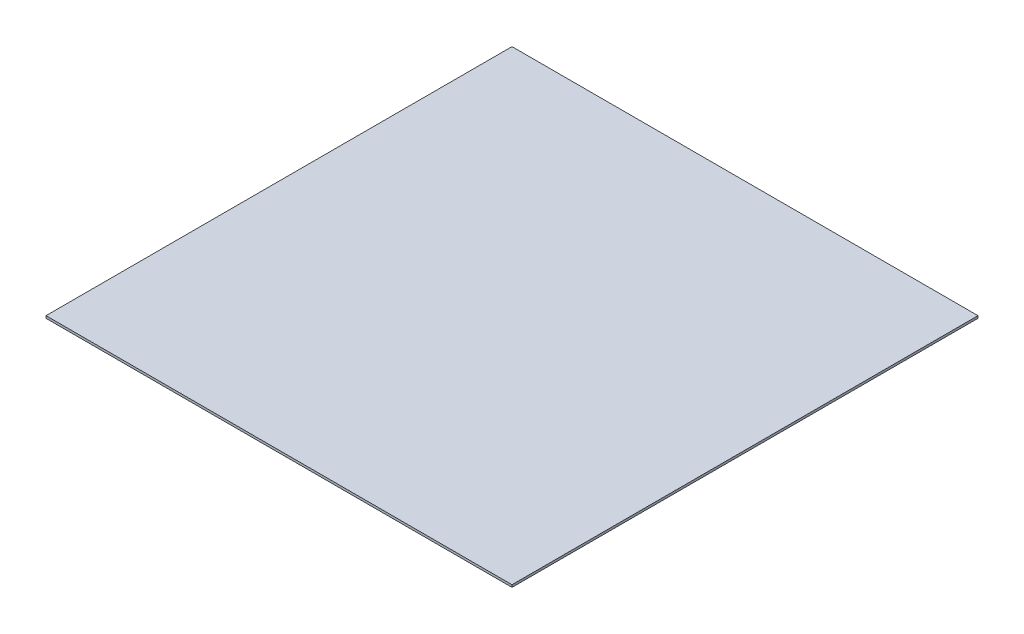
SolidWorks part; units mm, degrees
ref_plane "前视基准面" through (0, 0, 0) normal (0, 0, 1) x (1, 0, 0)
ref_plane "上视基准面" through (0, 0, 0) normal (0, 1, 0) x (1, 0, 0)
ref_plane "右视基准面" through (0, 0, 0) normal (1, 0, 0) x (0, 0, -1)
other "Configuration Table"
sketch "草图1" plane through (0, 0, 0) normal (0, 1, 0) x (1, 0, 0)
  line L1 (-1000, -1000) -> (1000, -1000)
  line L2 (-1000, -1000) -> (-1000, 1000)
  line L3 (-1000, 1000) -> (1000, 1000)
  line L4 (1000, -1000) -> (1000, 1000)
  dimension "D1" = 2000
  dimension "D2" = 2000
  dimension "D3" = 1000
  dimension "D4" = 1000
extrude "凸台-拉伸1" add sketch "草图1" along normal blind 10
